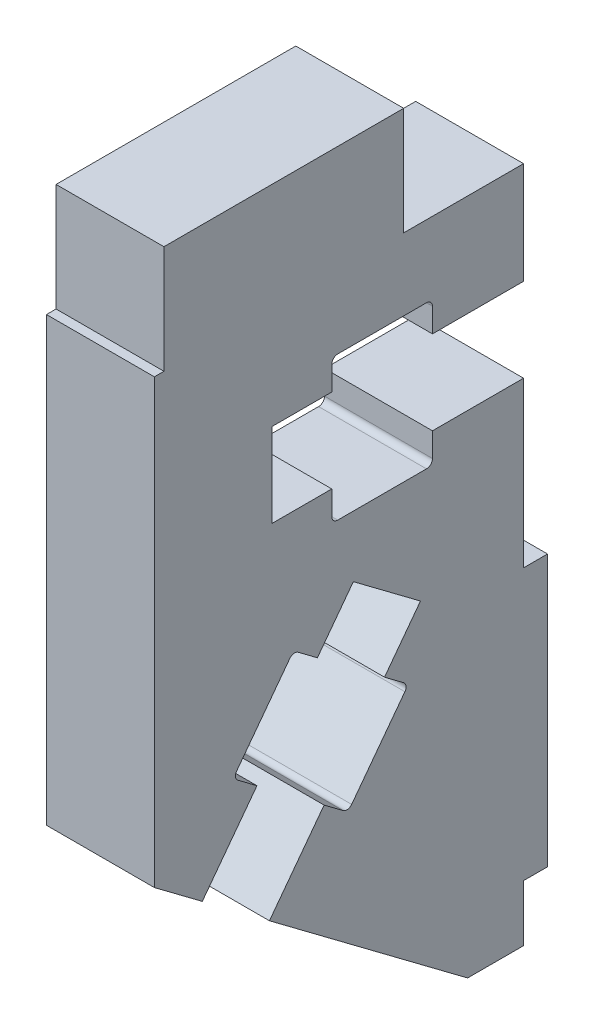
SolidWorks part; units mm, degrees
ref_plane "Front Plane" through (0, 0, 0) normal (0, 0, 1) x (1, 0, 0)
ref_plane "Top Plane" through (0, 0, 0) normal (0, 1, 0) x (1, 0, 0)
ref_plane "Right Plane" through (0, 0, 0) normal (1, 0, 0) x (0, 0, -1)
sketch "Sketch1" plane through (0, 0, 0) normal (1, 0, 0) x (0, 0, -1)
  line L0 (0, 0) -> (0, -30)
  line L1 (0, -30) -> (-40, 0)
  line L2 (-40, 0) -> (0, 0)
  dimension "D1" = 40
  dimension "D2" = 30
extrude "Boss-Extrude1" add sketch "Sketch1" along normal blind 4.5
sketch "Sketch2" plane through (4.5, 0, 0) normal (1, 0, 0) x (0, 0, -1)
  line L0 (0, -25.9) -> (1, -25.9)
  line L1 (0, -30) -> (0, 0) construction
  line L2 (1, -25.9) -> (1, -14.6)
  line L3 (1, -14.6) -> (0, -14.6)
  line L4 (0, -14.6) -> (0, -25.9)
  line L5 (1, -20.25) -> (0, -20.25) construction
  line L6 (0, -14.5) -> (4.5, -14.5) construction
  line L7 (0, -26) -> (4.5, -26) construction
  dimension "D2" = 1
  dimension "D3" = 0.1
  dimension "D1" = 0.1
extrude "Boss-Extrude2" add sketch "Sketch2" against normal through all
sketch "Sketch3" plane through (4.5, 0, 0) normal (1, 0, 0) x (0, 0, -1)
  line L0 (0, -6) -> (-10.5, -6) construction
  line L1 (0, -14.6) -> (0, 0) construction
  line L2 (-10.5, -7.75) -> (-10.5, -4.25) construction
  line L3 (-10.5, -4.25) -> (0, -4.25) construction
  line L4 (0, -4.25) -> (-3.8, -4.25)
  line L5 (-3.8, -4.25) -> (-3.8, -3.25)
  line L6 (-4.05, -3) -> (-7.75, -3)
  line L7 (-8, -3.25) -> (-8, -4.25)
  line L8 (-8, -4.25) -> (-10.5, -4.25)
  line L9 (-10.5, -4.25) -> (-10.5, -7.75)
  line L10 (0, -4.25) -> (0, -7.75)
  line L12 (-10.5, -7.75) -> (0, -7.75) construction
  line L13 (-8, -7.75) -> (-10.5, -7.75)
  line L14 (-8, -8.75) -> (-8, -7.75)
  line L15 (-4.05, -9) -> (-7.75, -9)
  line L16 (-3.8, -7.75) -> (-3.8, -8.75)
  line L17 (0, -7.75) -> (-3.8, -7.75)
  arc A0 (-3.8, -3.25) -> (-4.05, -3) centre (-4.05, -3.25) ccw
  arc A1 (-7.75, -3) -> (-8, -3.25) centre (-7.75, -3.25) ccw
  arc A2 (-7.75, -9) -> (-8, -8.75) centre (-7.75, -8.75) cw
  arc A3 (-3.8, -8.75) -> (-4.05, -9) centre (-4.05, -8.75) cw
  point P15 (-3.8, -3)
  point P18 (-8, -3)
  point P29 (-8, -9)
  point P30 (-3.8, -9)
  dimension "D7" = 0.25
  dimension "D1" = 10.5
  dimension "D2" = 1.75
  dimension "D3" = 4.2
  dimension "D4" = 3
  dimension "D5" = 8
  dimension "D6" = 6
extrude "Cut-Extrude1" cut sketch "Sketch3" against normal through all
sketch "Sketch4" plane through (4.5, 0, 0) normal (1, 0, 0) x (0, 0, -1)
  line L0 (-13.4, -19.95) -> (-7.1, -11.55) construction
  line L1 (-40, 0) -> (0, -30) construction
  line L2 (-7.1, -11.55) -> (-4.3, -13.65) construction
  line L3 (-5.7, -12.6) -> (-12, -21) construction
  line L4 (-10.6, -22.05) -> (-13.4, -19.95)
  line L5 (-13.4, -19.95) -> (-11.12, -16.91)
  line L6 (-11.12, -16.91) -> (-11.92, -16.31)
  line L7 (-11.97, -15.96) -> (-9.75, -13)
  line L8 (-9.4, -12.95) -> (-8.6, -13.55)
  line L9 (-8.6, -13.55) -> (-7.1, -11.55)
  line L10 (-7.1, -11.55) -> (-4.3, -13.65)
  line L11 (0, 0) -> (-40, 0) construction
  line L12 (-10.6, -22.05) -> (-4.3, -13.65) construction
  line L13 (-5.8, -15.65) -> (-4.3, -13.65)
  line L14 (-5, -16.25) -> (-5.8, -15.65)
  line L15 (-7.17, -19.56) -> (-4.95, -16.6)
  line L16 (-8.32, -19.01) -> (-7.52, -19.61)
  line L17 (-10.6, -22.05) -> (-8.32, -19.01)
  arc A0 (-11.92, -16.31) -> (-11.97, -15.96) centre (-11.77, -16.11) cw
  arc A1 (-9.75, -13) -> (-9.4, -12.95) centre (-9.55, -13.15) cw
  arc A2 (-4.95, -16.6) -> (-5, -16.25) centre (-5.15, -16.45) ccw
  arc A3 (-7.52, -19.61) -> (-7.17, -19.56) centre (-7.37, -19.41) ccw
  point P14 (-12.12, -16.16)
  point P17 (-9.6, -12.8)
  point P28 (-4.8, -16.4)
  point P29 (-7.32, -19.76)
  dimension "D7" = 0.25
  dimension "D1" = 10.5
  dimension "D2" = 1.75
  dimension "D3" = 4.2
  dimension "D4" = 3
  dimension "D5" = 8
  dimension "D6" = 21
extrude "Cut-Extrude2" cut sketch "Sketch4" against normal through all
sketch "Sketch5" plane through (4.5, 0, 0) normal (1, 0, 0) x (0, 0, -1)
  line L0 (-15.4, -18.45) -> (-15.4, 0)
  line L1 (-40, 0) -> (-13.4, -19.95) construction
  line L2 (0, 0) -> (-40, 0) construction
  line L3 (-15.4, 0) -> (-40, 0)
  line L4 (-40, 0) -> (-15.4, -18.45)
  dimension "D1" = 2
extrude "Cut-Extrude3" cut sketch "Sketch5" against normal through all
sketch "Sketch6" plane through (0, 0, 10.5) normal (0, 0, -1) x (-1, 0, 0)
  line L0 (-2.25, -4.25) -> (-2.25, -7.75) construction
  line L1 (0, -4.25) -> (-4.5, -4.25) construction
  line L2 (0, -7.75) -> (-4.5, -7.75) construction
  circle A0 centre (-2.25, -6) radius 1.5
  dimension "D1" = 3
sketch "Sketch7" plane through (0, -10.8, 8.1) normal (0, -0.8, 0.6) x (1, 0, 0)
  line L0 (2.25, -1.25) -> (2.25, -4.75) construction
  line L1 (0, -1.25) -> (4.5, -1.25) construction
  line L2 (0, -4.75) -> (4.5, -4.75) construction
  circle A0 centre (2.25, -3) radius 1.75
sketch "Sketch8" plane through (4.5, 0, 0) normal (1, 0, 0) x (0, 0, -1)
  line L0 (-10, 4.5) -> (-10, 0) construction
  line L1 (-15, 0) -> (-5, 0)
  line L2 (-15, 0) -> (-15, 4.5)
  line L3 (-15, 4.5) -> (-5, 4.5)
  line L4 (-5, 0) -> (-5, 4.5)
  line L5 (0, 0) -> (-15.4, 0) construction
  dimension "D1" = 10
  dimension "D2" = 4.5
  dimension "D3" = 10
extrude "Boss-Extrude3" add sketch "Sketch8" against normal through all
sketch "Sketch10" plane through (4.5, 0, 0) normal (1, 0, 0) x (0, 0, -1)
  line L0 (0, -28.25) -> (-2.3333, -28.25)
  line L1 (0, -30) -> (0, -25.9) construction
  line L2 (-10.6, -22.05) -> (0, -30) construction
  line L3 (-2.3333, -28.25) -> (0, -30)
  line L4 (0, -30) -> (0, -28.25)
  line L5 (4.5, -28.25) -> (0, -28.25) construction
  dimension "D1" = 0
extrude "Cut-Extrude4" cut sketch "Sketch10" against normal through all contours L0 L3 L4
equation "\"X-ROD-SPACING\"=45"
equation "\"Y-ROD-SPACING\"=75"
equation "\"Z-ROD-SPACING\"=17.5"
equation "\"Y-BED-OFFSET\"=2"
equation "\"Y-BED-ROD-INSET\"=3.5"
equation "\"Y-BED-SCREW-SPACING\"=209"
equation "\"Y-BED-SCREW-CUTOUT-SLOT-HEIGHT\"=2"
equation "\"T-SLOT-NUT-FILLET-RADIUS\"=0.25"
equation "\"T-SLOT-SCREW-SHAFT-RADIUS\"=1.75"
equation "\"T-SLOT-SCREW-SHAFT-CUTOUT-LENGTH\"=10.5"
equation "\"T-SLOT-NUT-DEPTH\"=4.2"
equation "\"T-SLOT-NUT-WIDTH\"=3"
equation "\"T-SLOT-NUT-END-DISTANCE\"=8"
equation "\"ACRYLIC-THICKNESS\"=10"
equation "\"ACRYLIC-THICKNESS2\"=4.5"
equation "\"ACRYLIC-TAB-CUTOUT-SIZE\"=\"ACRYLIC-THICKNESS\"+\"ACRYLIC-TAB-TOLERANCE\"*2"
equation "\"ACRYLIC-TAB-TOLERANCE\"=.1"
equation "\"ACRYLIC-TAB-WIDTH\"=\"ACRYLIC-THICKNESS\""
equation "\"ACRYLIC-M3-HOLE\"=3.1"
equation "\"SMOOTHROD-CAP-SCREW-DISTANCE\"=20"
equation "\"FRAME-WIDTH-INNER\"=370"
equation "\"NEMA17-HOLE-SPACING\"=31"
equation "\"NEMA17-CENTRAL-CUTOUT\"=22.5"
equation "\"Z-BRACKET-REACH\"=55"
equation "\"Z-ROD-INSET\"=16"
equation "\"TOP-BRACKET-SPACING\"=40"
equation "\"SMOOTHROD-X-LENGTH\"=350"
equation "\"SMOOTHROD-Y-LENGTH\"=350"
equation "\"SMOOTHROD-Z-LENGTH\"=350"
equation "\"SMOOTHROD-TIGHTENING-HEADROOM\"=.25"
equation "\"LEADSCREW-Z-LENGTH\"=300"
equation "\"SCREW-LENGTH-FRAME\"=\"ACRYLIC-THICKNESS\" + 10"
equation "\"SCREW-LENGTH-MOTOR\"=\"ACRYLIC-THICKNESS\" + 5"
equation "\"SCREW-LENGTH-EXTRUDER\"=28"
equation "\"SCREW-HEAD-RADIUS\"=6"
equation "\"PRINTED-M3-HOLE\"=3.5"
equation "\"PRINTED-X-SMOOTHROD-DIAMETER\"=8.2"
equation "\"PRINTED-X-SMOOTHROD-CUTOUT\"=10"
equation "\"PRINTED-X-BASE-HEIGHT\"=10"
equation "\"PRINTED-LM8UU-CUTOUT-SIZE\"=15.25"
equation "\"PRINTED-LM8UU-CUTOUT-LENGTH\"=24.5"
equation "\"PRINTED-X-IDLER-HEIGHT\"=16"
equation "\"PRINTED-M3-NUT-AF\"=6.25"
equation "\"PSU-MOUNTING-WIDTH\"=95"
equation "\"PSU-MOUNTING-HEIGHT\"=177"
equation "\"Y-BELT-TO-ROD-DISTANCE\"=20"
equation "\"SPOOL-HOLDER-ROD-SPACING\"=150"
equation "\"ACRYLIC-X-CARRIAGE-WIDTH\"=55"
equation "\"ACRYLIC-X-CARRIAGE-HEIGHT\"=75"
equation "\"ACRYLIC-X-CARRIAGE-LM8UU-CUTOUT-WIDTH\"=24.25"
equation "\"ACRYLIC-X-CARRIAGE-LM8UU-CUTOUT-HEIGHT\"=11.5"
equation "\"ACRYLIC-X-CARRIAGE-SCREW-SPACING-X\"=15"
equation "\"ACRYLIC-X-CARRIAGE-SCREW-SPACING-Y\"=33"
equation "\"ACRYLIC-X-CARRIAGE-CENTER-TAB-SPACING\"=14"
equation "\"ACRYLIC-X-CARRIAGE-EXTRUDER-OFFSET\"=26"
equation "\"ACRYLIC-X-CARRIAGE-EXTRUDER-ANGLE\"=90"
equation "\"ACRYLIC-X-CARRIAGE-EXTRUDER-SHELF-DEPTH\"=\"ACRYLIC-X-CARRIAGE-EXTRUDER-OFFSET\" + 28"
equation "\"ACRYLIC-X-CARRIAGE-EXTRUDER-BRACE-SPACING\"=23"
equation "\"ACRYLIC-X-CARRIAGE-EXTRUDER-BRACE-TAB-OFFSET\"=20"
equation "\"ACRYLIC-X-CARRIAGE-EXTRUDER-BRACE-HEIGHT\"=35"
equation "\"ACRYLIC-X-CARRIAGE-EXTRUDER-BRACE-SCREW-SPACING\"=22"
equation "\"ACRYLIC-X-CARRIAGE-DUAL-WIDTH-MULTIPLIER\"=1.65"
equation "\"ACRYLIC-X-CARRIAGE-DUAL-HOTEND-SPACING\"=42"
equation "\"ACRYLIC-X-CARRIAGE-DUAL-WIDTH\"=75"
equation "\"ACRYLIC-X-CARRIAGE-DUAL-FAN-OFFSET\"=52"
equation "\"ACRYLIC-X-CARRIAGE-DUAL-FAN-HEIGHT\"=20"
equation "\"ACRYLIC-X-CARRIAGE-DUAL-HOTEND-SEPARATION\"=36"
equation "\"ACRYLIC-X-CARRIAGE-DUAL-MOUNT-PLATE-DEPTH\"=75"
equation "\"ACRYLIC-X-CARRIAGE-DUAL-MOUNT-BRACE-WIDTH\"=33"
equation "\"ACRYLIC-X-CARRIAGE-DUAL-MOUNT-SCREW-WIDTH\"=40"
equation "\"BLOWER-FAN-WIDTH\"=15"
equation "\"D1@Boss-Extrude1\"=\"ACRYLIC-THICKNESS2\""
equation "\"D1@Sketch2\"=\"ACRYLIC-TAB-TOLERANCE\""
equation "\"D1@Sketch3\"=\"T-SLOT-SCREW-SHAFT-CUTOUT-LENGTH\""
equation "\"D2@Sketch3\"=\"T-SLOT-SCREW-SHAFT-RADIUS\""
equation "\"D3@Sketch3\"=\"T-SLOT-NUT-DEPTH\""
equation "\"D4@Sketch3\"=\"T-SLOT-NUT-WIDTH\""
equation "\"D5@Sketch3\"=\"T-SLOT-NUT-END-DISTANCE\""
equation "\"D7@Sketch3\"=\"T-SLOT-NUT-FILLET-RADIUS\""
equation "\"D1@Sketch4\"=\"T-SLOT-SCREW-SHAFT-CUTOUT-LENGTH\""
equation "\"D2@Sketch4\"=\"T-SLOT-SCREW-SHAFT-RADIUS\""
equation "\"D3@Sketch4\"=\"T-SLOT-NUT-DEPTH\""
equation "\"D4@Sketch4\"=\"T-SLOT-NUT-WIDTH\""
equation "\"D5@Sketch4\"=\"T-SLOT-NUT-END-DISTANCE\""
equation "\"D7@Sketch4\"=\"T-SLOT-NUT-FILLET-RADIUS\""
equation "\"D1@Sketch8\"=\"ACRYLIC-TAB-WIDTH\""
equation "\"D2@Sketch8\"=\"ACRYLIC-THICKNESS2\""
equation "\"D3@Sketch2\"=\"ACRYLIC-TAB-TOLERANCE\""
